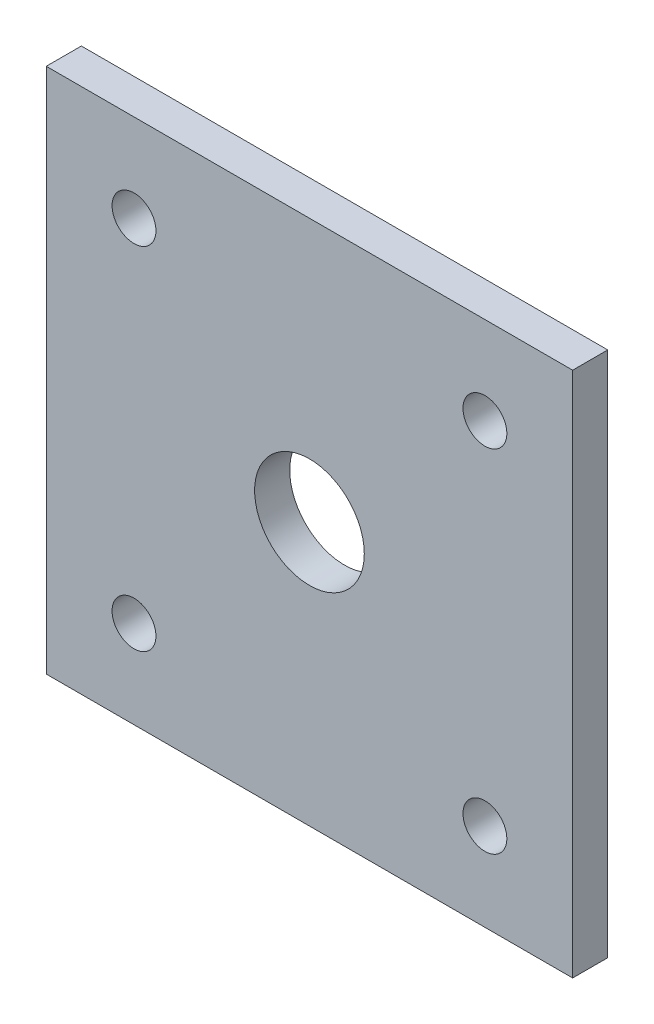
SolidWorks part; units mm, degrees
ref_plane "Front Plane" through (0, 0, 0) normal (0, 0, 1) x (1, 0, 0)
ref_plane "Top Plane" through (0, 0, 0) normal (0, 1, 0) x (1, 0, 0)
ref_plane "Right Plane" through (0, 0, 0) normal (1, 0, 0) x (0, 0, -1)
sketch "Sketch2" plane through (0, 0, 0) normal (0, 0, 1) x (1, 0, 0)
  line L1 (-60, -60) -> (60, -60)
  line L2 (-60, -60) -> (-60, 60)
  line L3 (-60, 60) -> (60, 60)
  line L4 (60, -60) -> (60, 60)
  line L5 (-60, -60) -> (60, 60) construction
  line L6 (-60, 60) -> (60, -60) construction
  point P0 (0, 0)
  dimension "D1" = 120
extrude "Boss-Extrude1" add sketch "Sketch2" along normal blind 8
sketch "Sketch3" plane through (0, 0, 8) normal (0, 0, 1) x (1, 0, 0)
  circle A0 centre (0, 0) radius 7.62
sketch "Sketch4" plane through (0, 0, 8) normal (0, 0, 1) x (1, 0, 0)
  circle A1 centre (0, 0) radius 12.5
  dimension "D1" = 25
extrude "Cut-Extrude1" cut sketch "Sketch4" against normal through all contours A1
sketch "Sketch6" plane through (0, 0, 8) normal (0, 0, 1) x (1, 0, 0)
  line L0 (-60, 60) -> (-60, -60) construction
  line L1 (60, 60) -> (-60, 60) construction
  circle A0 centre (-40, 40) radius 5
  dimension "D1" = 20
  dimension "D3" = 10
  dimension "D2" = 20
extrude "Cut-Extrude2" cut sketch "Sketch6" against normal through all
pattern_linear "LPattern1" count 2 spacing 80 along (1, 0, 0) count 2 spacing 80 along (0, -1, 0) of "Cut-Extrude2"
